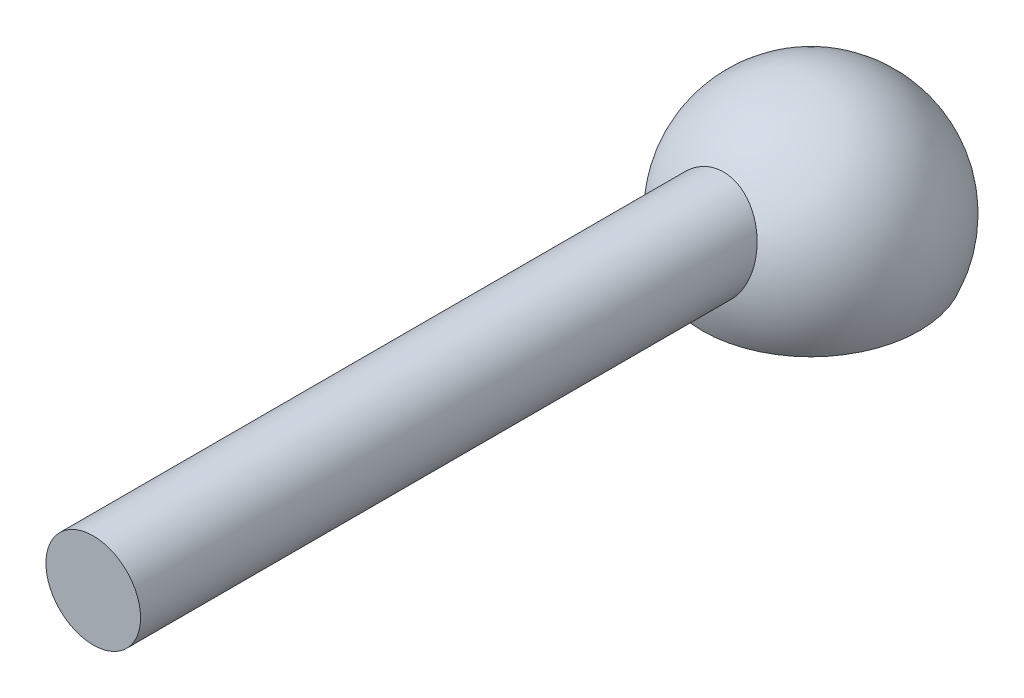
SolidWorks part; units mm, degrees
ref_plane "Front Plane" through (0, 0, 0) normal (0, 0, 1) x (1, 0, 0)
ref_plane "Top Plane" through (0, 0, 0) normal (0, 1, 0) x (1, 0, 0)
ref_plane "Right Plane" through (0, 0, 0) normal (1, 0, 0) x (0, 0, -1)
sketch "Sketch1" plane through (0, 0, 0) normal (0, 0, 1) x (1, 0, 0)
  line L0 (0, 0) -> (74.6252, 0) construction
  line L1 (23.5649, 0) -> (29.3126, 0)
  line L2 (45.3126, 0) -> (51.0603, 0)
  line L3 (37.3126, 0) -> (37.3126, 27.6379) construction
  line L4 (37.3126, 21) -> (37.3126, 16)
  arc A0 (37.3126, 21) -> (23.5649, 0) centre (37.3126, 6) ccw
  arc A1 (37.3126, 16) -> (29.3126, 0) centre (37.3126, 6) ccw
  dimension "D1" = 5
  dimension "D2" = 30
  dimension "D3" = 6
revolve "Revolve1" add sketch "Sketch1" angle 360 about L4
sketch "Sketch2" plane through (0, 0, 0) normal (0, 0, 1) x (1, 0, 0)
  circle A0 centre (37.3126, 10.1236) radius 6
  dimension "D1" = 12
extrude "Boss-Extrude1" add sketch "Sketch2" along normal blind 91
